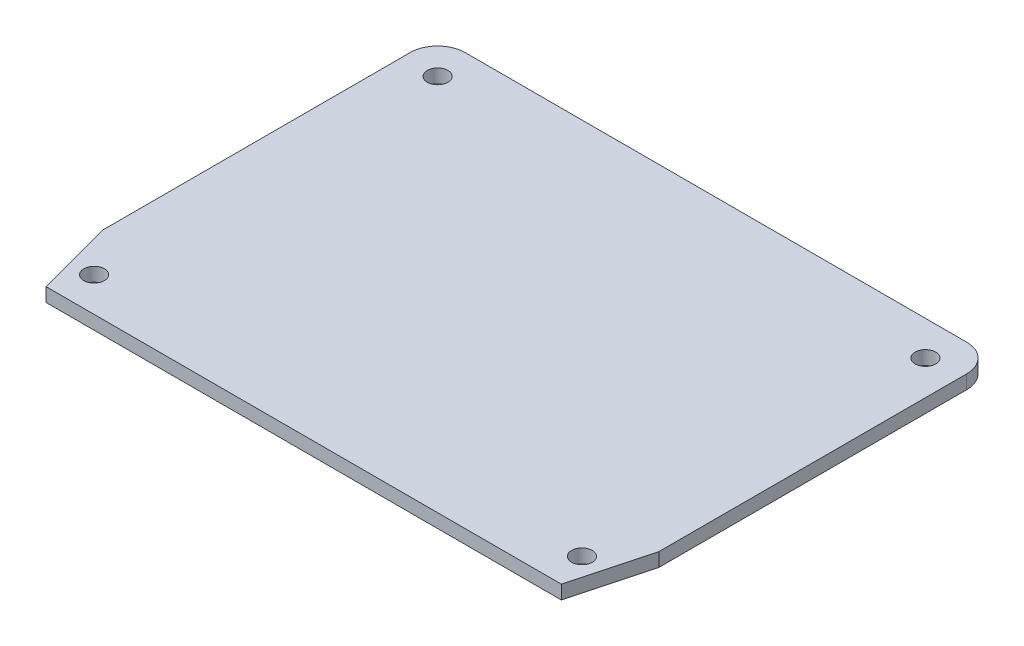
SolidWorks part; units mm, degrees
ref_plane "Front Plane" through (0, 0, 0) normal (0, 0, 1) x (1, 0, 0)
ref_plane "Top Plane" through (0, 0, 0) normal (0, 1, 0) x (1, 0, 0)
ref_plane "Right Plane" through (0, 0, 0) normal (1, 0, 0) x (0, 0, -1)
sketch "Sketch1" plane through (0, 0, 0) normal (0, 1, 0) x (1, 0, 0)
  line L1 (-40.5, -30) -> (40.5, -30)
  line L2 (-40.5, -30) -> (-40.5, 30)
  line L3 (-40.5, 30) -> (40.5, 30)
  line L4 (40.5, -30) -> (40.5, 30)
  line L5 (-40.5, -30) -> (40.5, 30) construction
  line L6 (-40.5, 30) -> (40.5, -30) construction
  point P0 (0, 0)
  dimension "D1" = 81
  dimension "D2" = 60
extrude "Boss-Extrude1" add sketch "Sketch1" along normal blind 2
sketch "Sketch2" plane through (0, 2, 0) normal (0, 1, 0) x (1, 0, 0)
  line L0 (-40.5, 30) -> (-40.5, -30) construction
  line L1 (40.5, 30) -> (-40.5, 30) construction
  line L2 (-40.5, -30) -> (40.5, -30) construction
  line L3 (40.5, -30) -> (40.5, 30) construction
  circle A0 centre (-35.5, -25) radius 1.5
  circle A1 centre (35.5, -25) radius 1.5
  circle A2 centre (-35.5, 25) radius 1.5
  circle A3 centre (35.5, 25) radius 1.5
  dimension "D1" = 3
  dimension "D2" = 71
  dimension "D3" = 5
  dimension "D4" = 5
  dimension "D5" = 5
  dimension "D6" = 5
extrude "Cut-Extrude1" cut sketch "Sketch2" against normal through all
fillet "Fillet1" radius 4 2 edges at (-40.5, 1, -30) (40.5, 1, -30)
chamfer "Chamfer1" distance 3 angle 75 1 edges at (40.5, 1, 30)
chamfer "Chamfer2" distance 3 angle 75 1 edges at (-40.5, 1, 30)
